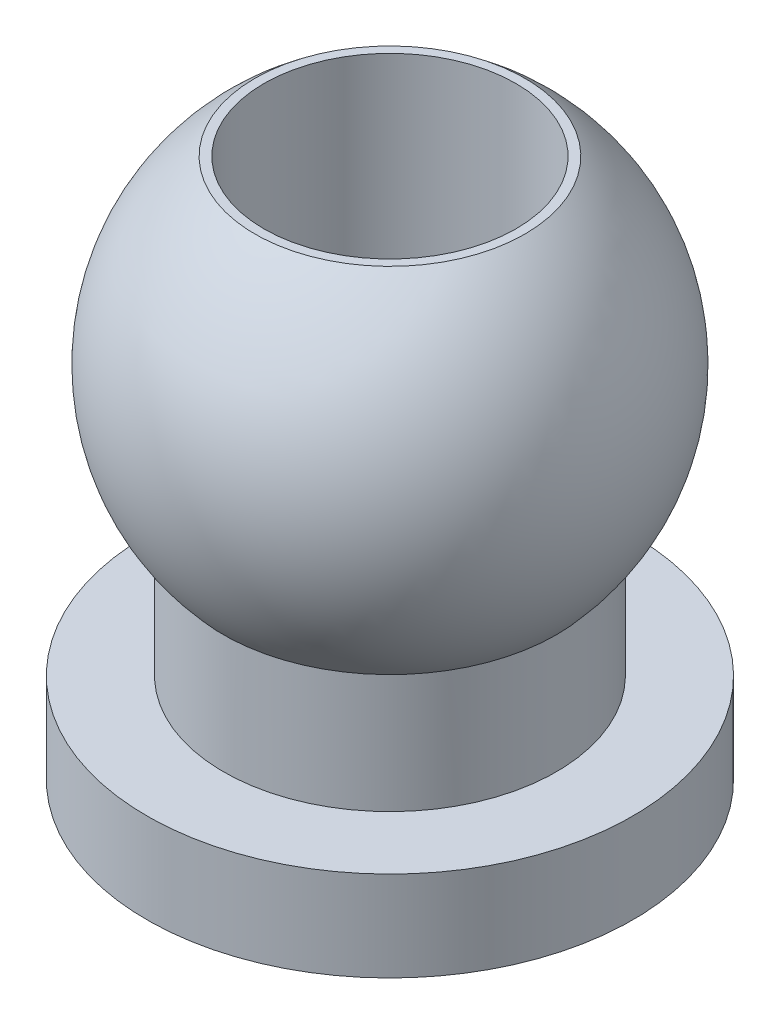
SolidWorks part; units mm, degrees
ref_plane "Plan de face" through (0, 0, 0) normal (0, 0, 1) x (1, 0, 0)
ref_plane "Plan de dessus" through (0, 0, 0) normal (0, 1, 0) x (1, 0, 0)
ref_plane "Plan de droite" through (0, 0, 0) normal (1, 0, 0) x (0, 0, -1)
sketch "Esquisse1" plane through (0, 0, 0) normal (0, 0, 1) x (1, 0, 0)
  line L0 (1.5, 2) -> (1.4, 2)
  line L1 (1.4, 2) -> (1.4, -4)
  line L2 (1.4, -4) -> (2.7, -4)
  line L3 (2.7, -4) -> (2.7, -3)
  line L4 (2.7, -3) -> (1.85, -3)
  line L5 (1.85, -3) -> (1.85, -1.6815)
  line L6 (0, 2) -> (0, -4) construction
  arc A0 (1.85, -1.6815) -> (1.5, 2) centre (0, 0) ccw
  dimension "D7" = 2.5
  dimension "D1" = 2.8
  dimension "D2" = 6
  dimension "D3" = 5.4
  dimension "D4" = 3.7
  dimension "D5" = 1
  dimension "D6" = 2
  dimension "D8" = 1.3185
revolve "Révolution1" add sketch "Esquisse1" angle 360 about L6
